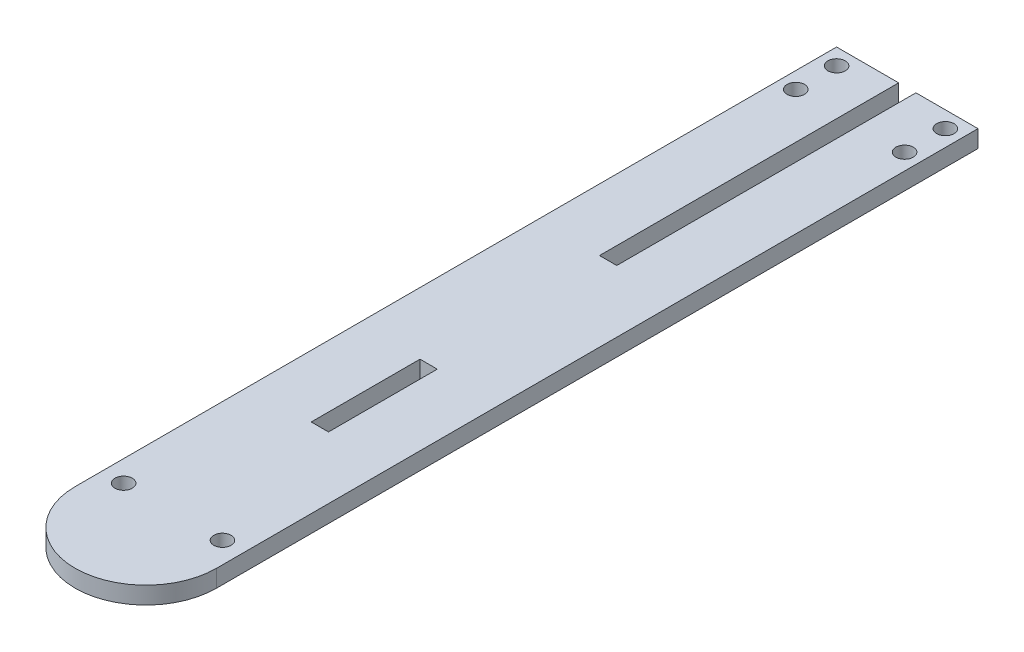
SolidWorks part; units mm, degrees
ref_plane "Front Plane" through (0, 0, 0) normal (0, 0, 1) x (1, 0, 0)
ref_plane "Top Plane" through (0, 0, 0) normal (0, 1, 0) x (1, 0, 0)
ref_plane "Right Plane" through (0, 0, 0) normal (1, 0, 0) x (0, 0, -1)
sketch "Sketch1" plane through (0, 0, 0) normal (0, 1, 0) x (1, 0, 0)
  line L1 (-14.5875, 0) -> (-14.5875, -140)
  line L2 (11.4125, 0) -> (11.4125, -140)
  line L3 (-14.5875, 0) -> (-3.175, 0)
  line L5 (-3.175, 0) -> (-3.175, -55)
  line L6 (-3.175, -55) -> (0, -55)
  line L7 (0, 0) -> (0, -55)
  line L8 (11.4125, 0) -> (0, 0)
  line L9 (0, -43) -> (-3.175, -43) construction
  line L10 (-3.175, -88) -> (0, -88)
  line L11 (-3.175, -88) -> (-3.175, -108)
  line L12 (-3.175, -108) -> (0, -108)
  line L13 (0, -88) -> (0, -108)
  arc A0 (-14.5875, -140) -> (11.4125, -140) centre (-1.5875, -140) ccw
  point P6 (-8.8812, 0)
  dimension "D1" = 26
  dimension "D2" = 140
  dimension "D3" = 3.175
  dimension "D4" = 55
  dimension "D5" = 20
  dimension "D6" = 45
  dimension "D7" = 12
extrude "Boss-Extrude1" add sketch "Sketch1" along normal blind 3.175
sketch "Sketch4" plane through (0, 0, 0) normal (0, -1, 0) x (1, 0, 0)
  circle A0 centre (8.4125, 3) radius 1.6 construction
  circle A1 centre (8.4125, 10.5) radius 1.6 construction
  circle A2 centre (-11.5875, 10.5) radius 1.6 construction
  circle A3 centre (-11.5875, 3) radius 1.6 construction
  circle A4 centre (8.4125, 3) radius 1.6
  circle A5 centre (8.4125, 10.5) radius 1.6
  circle A6 centre (-11.5875, 10.5) radius 1.6
  circle A7 centre (-11.5875, 3) radius 1.6
extrude "Cut-Extrude2" cut sketch "Sketch4" against normal through all both and the other way through all
sketch "Sketch5" plane through (0, 3.175, 0) normal (0, 1, 0) x (1, 0, 0)
  circle A0 centre (-10.675, -135) radius 1.6 construction
  circle A1 centre (7.5, -135) radius 1.6 construction
  circle A2 centre (-10.675, -135) radius 1.6
  circle A3 centre (7.5, -135) radius 1.6
extrude "Cut-Extrude3" cut sketch "Sketch5" against normal through all both and the other way through all
